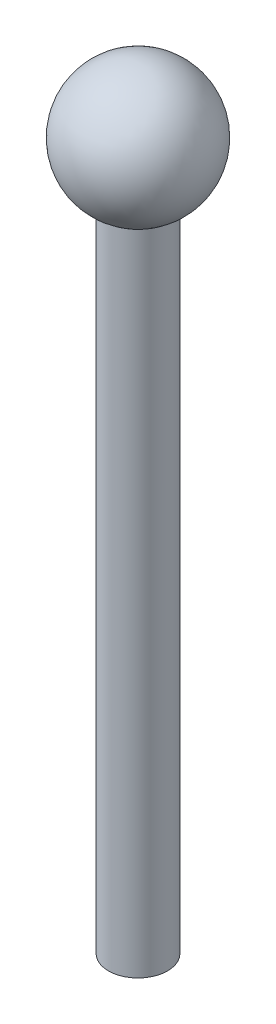
SolidWorks part; units mm, degrees
ref_plane "Plan de face" through (0, 0, 0) normal (0, 0, 1) x (1, 0, 0)
ref_plane "Plan de dessus" through (0, 0, 0) normal (0, 1, 0) x (1, 0, 0)
ref_plane "Plan de droite" through (0, 0, 0) normal (1, 0, 0) x (0, 0, -1)
sketch "Esquisse1" plane through (0, 0, 0) normal (0, 0, 1) x (1, 0, 0)
  line L0 (0, 0) -> (0, 118.9016) construction
  line L1 (0, 0) -> (-4.5565, 0)
  line L2 (-4.5565, 0) -> (-4.5565, 100)
  line L3 (0, 0) -> (0, 118.9016)
  line L4 (0, 118.9016) -> (-26.3661, 118.9016) construction
  arc A0 (-4.5565, 100) -> (0, 118.9016) centre (0, 108.9016) cw
  dimension "D1" = 10
  dimension "D2" = 100
revolve "Révolution1" add sketch "Esquisse1" angle 360 about L3
